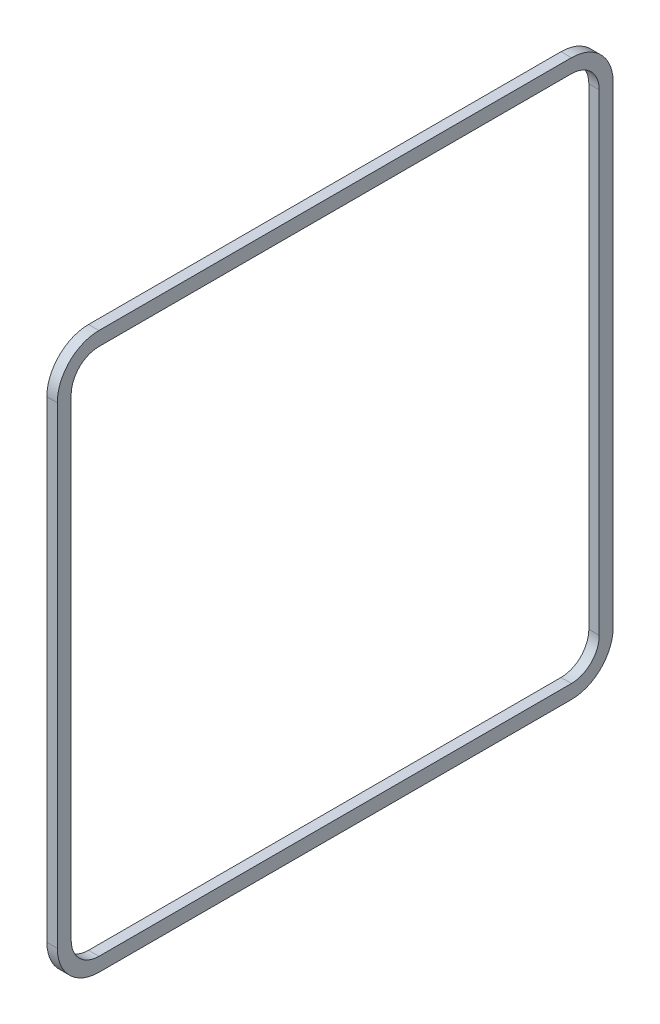
SolidWorks part; units mm, degrees
material "Copper"
ref_plane "Front Plane" through (0, 0, 0) normal (0, 0, 1) x (1, 0, 0)
ref_plane "Top Plane" through (0, 0, 0) normal (0, 1, 0) x (1, 0, 0)
ref_plane "Right Plane" through (0, 0, 0) normal (1, 0, 0) x (0, 0, -1)
sketch "Sketch1" plane through (0, 0, 0) normal (1, 0, 0) x (0, 0, -1)
  line L0 (34, 38) -> (-34, 38)
  line L1 (34, -40) -> (-34, -40)
  line L2 (40, -34) -> (40, 34)
  line L3 (34, 40) -> (-34, 40)
  line L4 (-40, -34) -> (-40, 34)
  line L5 (40, -40) -> (-40, 40) construction
  line L6 (40, 40) -> (-40, -40) construction
  line L7 (-38, -34) -> (-38, 34)
  line L8 (34, -38) -> (-34, -38)
  line L9 (38, -34) -> (38, 34)
  arc A0 (-40, -34) -> (-34, -40) centre (-34, -34) ccw
  arc A1 (34, -40) -> (40, -34) centre (34, -34) ccw
  arc A2 (40, 34) -> (34, 40) centre (34, 34) ccw
  arc A3 (-40, 34) -> (-34, 40) centre (-34, 34) cw
  arc A4 (-38, 34) -> (-34, 38) centre (-34, 34) cw
  arc A5 (-38, -34) -> (-34, -38) centre (-34, -34) ccw
  arc A6 (34, -38) -> (38, -34) centre (34, -34) ccw
  arc A7 (38, 34) -> (34, 38) centre (34, 34) ccw
  point P0 (0, 0)
  dimension "D3" = 6
  dimension "D1" = 80
  dimension "D2" = 80
  dimension "D4" = 2
extrude "Boss-Extrude1" add sketch "Sketch1" along normal blind 1.5
